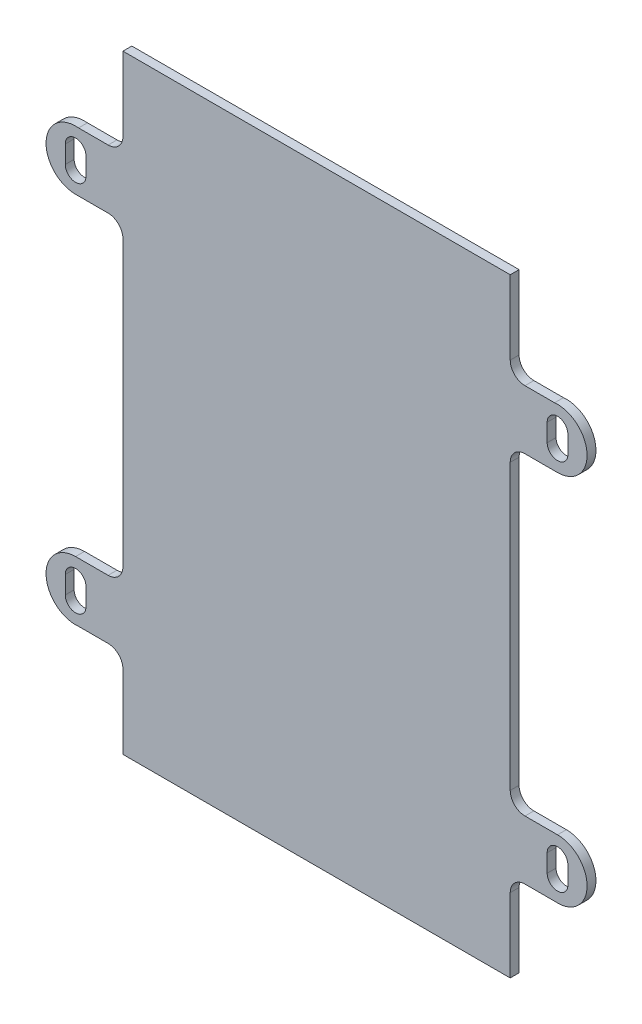
SolidWorks part; units mm, degrees
ref_plane "Front Plane" through (0, 0, 0) normal (0, 0, 1) x (1, 0, 0)
ref_plane "Top Plane" through (0, 0, 0) normal (0, 1, 0) x (1, 0, 0)
ref_plane "Right Plane" through (0, 0, 0) normal (1, 0, 0) x (0, 0, -1)
sketch "Sketch2" plane through (0, 0, 0) normal (0, 0, 1) x (1, 0, 0)
  line L0 (81.5, 60.0501) -> (81.5, 66.0501) construction
  line L1 (-65.5, -103) -> (65.5, -103)
  line L2 (-65.5, -103) -> (-65.5, -78)
  line L3 (-65.5, 103) -> (65.5, 103)
  line L4 (65.5, -103) -> (65.5, -78)
  line L5 (-65.5, -103) -> (65.5, 103) construction
  line L6 (-65.5, 103) -> (65.5, -103) construction
  line L7 (70.5, 73) -> (80.5, 73)
  line L9 (70.5, 53.0501) -> (81.5, 53.0501)
  line L10 (78, 60.0501) -> (78, 66.0501)
  line L11 (85, 60.0501) -> (85, 66.0501)
  line L12 (0, 0) -> (0, -103) construction
  line L13 (0, 0) -> (65.5, 0) construction
  line L14 (-81.5, 60.0501) -> (-81.5, 66.0501) construction
  line L15 (-78, 60.0501) -> (-78, 66.0501)
  line L16 (-85, 60.0501) -> (-85, 66.0501)
  line L17 (-70.5, 53.0501) -> (-81.5, 53.0501)
  line L19 (-70.5, 73) -> (-80.5, 73)
  line L20 (-81.5, -60.0501) -> (-81.5, -66.0501) construction
  line L21 (-78, -60.0501) -> (-78, -66.0501)
  line L22 (-85, -60.0501) -> (-85, -66.0501)
  line L23 (81.5, -60.0501) -> (81.5, -66.0501) construction
  line L24 (78, -60.0501) -> (78, -66.0501)
  line L25 (85, -60.0501) -> (85, -66.0501)
  line L26 (70.5, -53.0501) -> (81.5, -53.0501)
  line L28 (70.5, -73) -> (80.5, -73)
  line L30 (-70.5, -73) -> (-80.5, -73)
  line L31 (-70.5, -53.0501) -> (-81.5, -53.0501)
  line L32 (-65.5, 78) -> (-65.5, 103)
  line L33 (65.5, 78) -> (65.5, 103)
  line L34 (-65.5, -48.0501) -> (-65.5, 48.0501)
  line L35 (65.5, -48.0501) -> (65.5, 48.0501)
  arc A0 (81.5, 53.0501) -> (80.5, 73) centre (81.5, 63.0501) ccw
  arc A1 (78, 60.0501) -> (85, 60.0501) centre (81.5, 60.0501) ccw
  arc A2 (85, 66.0501) -> (78, 66.0501) centre (81.5, 66.0501) ccw
  arc A3 (-78, 60.0501) -> (-85, 60.0501) centre (-81.5, 60.0501) cw
  arc A4 (-85, 66.0501) -> (-78, 66.0501) centre (-81.5, 66.0501) cw
  arc A5 (-81.5, 53.0501) -> (-80.5, 73) centre (-81.5, 63.0501) cw
  arc A6 (-78, -60.0501) -> (-85, -60.0501) centre (-81.5, -60.0501) ccw
  arc A7 (-85, -66.0501) -> (-78, -66.0501) centre (-81.5, -66.0501) ccw
  arc A8 (78, -60.0501) -> (85, -60.0501) centre (81.5, -60.0501) cw
  arc A9 (85, -66.0501) -> (78, -66.0501) centre (81.5, -66.0501) cw
  arc A10 (81.5, -53.0501) -> (80.5, -73) centre (81.5, -63.0501) cw
  arc A11 (-81.5, -53.0501) -> (-80.5, -73) centre (-81.5, -63.0501) ccw
  arc A12 (-65.5, 48.0501) -> (-70.5, 53.0501) centre (-70.5, 48.0501) ccw
  arc A13 (-65.5, 78) -> (-70.5, 73) centre (-70.5, 78) cw
  arc A14 (-65.5, -48.0501) -> (-70.5, -53.0501) centre (-70.5, -48.0501) cw
  arc A15 (-70.5, -73) -> (-65.5, -78) centre (-70.5, -78) cw
  arc A16 (65.5, -48.0501) -> (70.5, -53.0501) centre (70.5, -48.0501) ccw
  arc A17 (65.5, -78) -> (70.5, -73) centre (70.5, -78) cw
  arc A18 (65.5, 48.0501) -> (70.5, 53.0501) centre (70.5, 48.0501) cw
  arc A19 (70.5, 73) -> (65.5, 78) centre (70.5, 78) cw
  point P0 (0, 0)
  point P13 (81.5, 63.0501)
  point P23 (-81.5, 63.0501)
  point P35 (-81.5, -63.0501)
  point P42 (81.5, -63.0501)
  point P59 (-65.5, 53.0501)
  point P62 (-65.5, 73)
  point P65 (-65.5, -53.0501)
  point P68 (-65.5, -73)
  point P71 (65.5, -53.0501)
  point P74 (65.5, -73)
  point P77 (65.5, 53.0501)
  point P80 (65.5, 73)
  dimension "D3" = 10
  dimension "D5" = 3.5
  dimension "D8" = 7
  dimension "D10" = 5
  dimension "D1" = 131
  dimension "D2" = 206
  dimension "D4" = 15
  dimension "D6" = 6
  dimension "D7" = 12.5
  dimension "D9" = 30
extrude "Boss-Extrude1" add sketch "Sketch2" along normal blind 3
